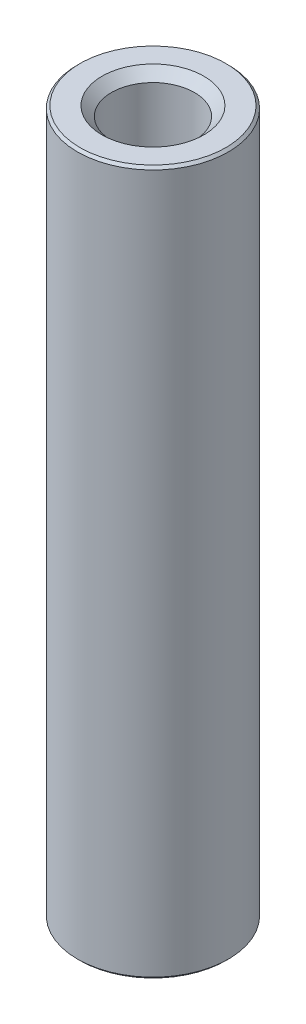
SolidWorks part; units mm, degrees
material "6061 Alloy"
ref_plane "前视基准面" through (0, 0, 0) normal (0, 0, 1) x (1, 0, 0)
ref_plane "上视基准面" through (0, 0, 0) normal (0, 1, 0) x (1, 0, 0)
ref_plane "右视基准面" through (0, 0, 0) normal (1, 0, 0) x (0, 0, -1)
other "Configuration Table"
sketch "草图1" plane through (0, 0, 0) normal (0, 1, 0) x (1, 0, 0)
  circle A0 centre (0, 0) radius 3
  dimension "D1" = 6
extrude "凸台-拉伸1" add sketch "草图1" along normal mid plane 28
sketch "草图4" plane through (0, 14, 0) normal (0, 1, 0) x (1, 0, 0)
  point P0 (0, 0)
hole_wizard "M4 Tapped Hole1" positions "草图4" profile "草图3" tap size "M4" standard "ISO" end condition through all
sketch "草图3" plane through (0, 14, 0) normal (1, 0, 0) x (0, 0, 1)
  line L0 (0, 0) -> (0, 28)
  line L1 (0, 28) -> (1.675, 28)
  line L2 (1.65, 27.975) -> (1.65, 0.375)
  line L3 (1.65, 0.375) -> (2.025, 0)
  line L5 (2.025, 0) -> (0, 0)
  line L6 (-1.65, 0.375) -> (-2.025, 0) construction
  line L7 (1.675, 28) -> (1.65, 27.975)
  line L8 (-1.675, 28) -> (-1.65, 27.975) construction
  line L11 (0, -6.35) -> (0, 107.95) construction
  dimension "Thru Tap Drill Dia." = 3.3
  dimension "Thru Tap Drill Depth" = 28
  dimension "Near C'Sink Dia." = 4.05
  dimension "Near C'Sink Angle" = 90
  dimension "Far C'Sink Dia." = 3.35
  dimension "Far C'Sink Angle" = 90
cosmetic thread "孔螺纹线1"
chamfer "倒角1" distance 0.1 angle 45 2 edges at (0, -14, 3) (0, 14, 3)
